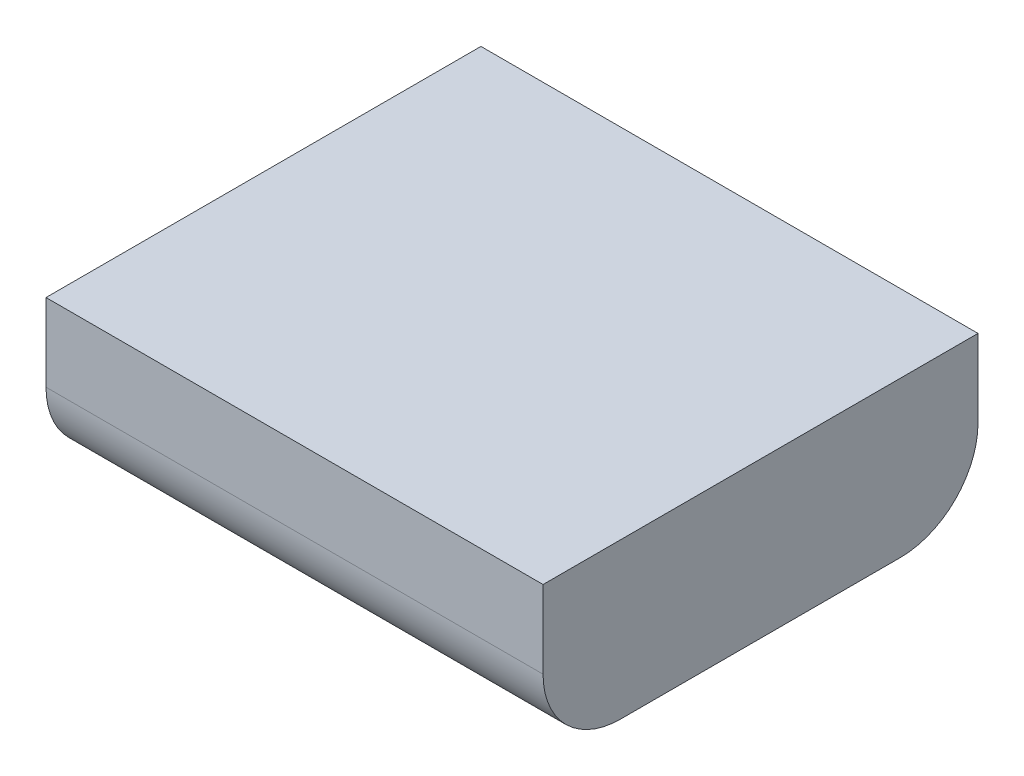
SolidWorks part; units mm, degrees
ref_plane "Front Plane" through (0, 0, 0) normal (0, 0, 1) x (1, 0, 0)
ref_plane "Top Plane" through (0, 0, 0) normal (0, 1, 0) x (1, 0, 0)
ref_plane "Right Plane" through (0, 0, 0) normal (1, 0, 0) x (0, 0, -1)
sketch "Sketch1" plane through (0, 0, 0) normal (1, 0, 0) x (0, 0, -1)
  line L1 (-14, -5) -> (14, -5)
  line L2 (-14, -5) -> (-14, 5)
  line L3 (-14, 5) -> (14, 5)
  line L4 (14, -5) -> (14, 5)
  line L5 (-14, -5) -> (14, 5) construction
  line L6 (-14, 5) -> (14, -5) construction
  point P0 (0, 0)
  dimension "D1" = 10
  dimension "D2" = 28
extrude "Boss-Extrude1" add sketch "Sketch1" along normal mid plane 32
fillet "Fillet1" radius 5 2 edges at (0, -5, -14) (0, -5, 14)
